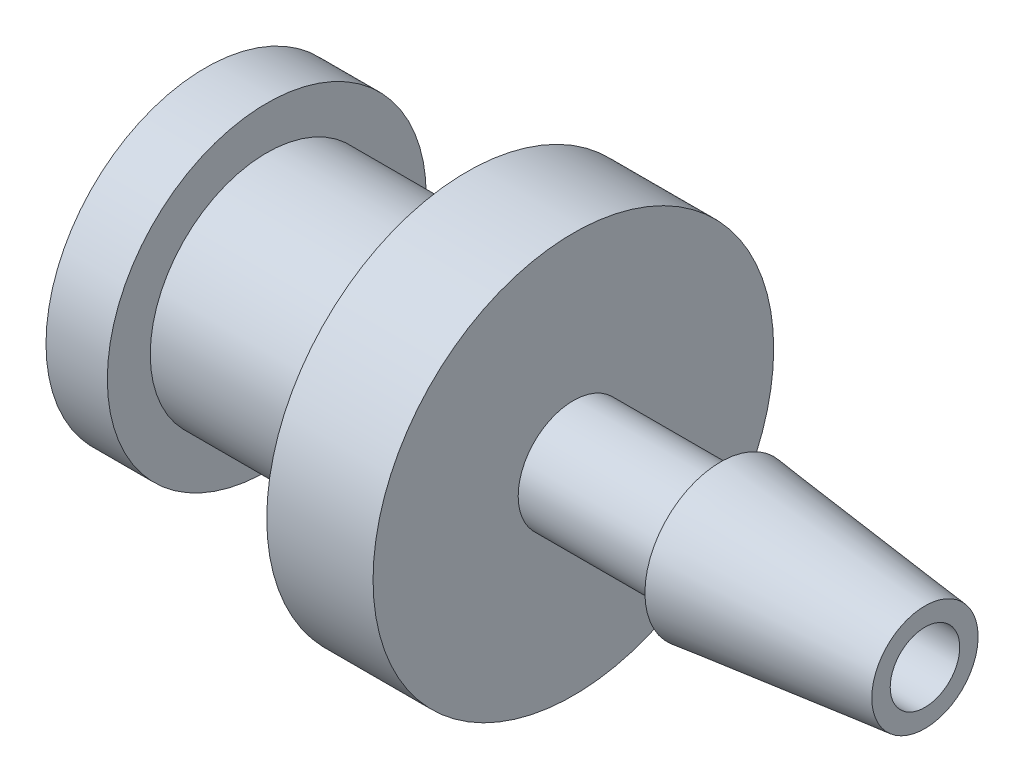
SolidWorks part; units mm, degrees
ref_plane "Płaszczyzna przednia" through (0, 0, 0) normal (0, 0, 1) x (1, 0, 0)
ref_plane "Płaszczyzna górna" through (0, 0, 0) normal (0, 1, 0) x (1, 0, 0)
ref_plane "Płaszczyzna prawa" through (0, 0, 0) normal (1, 0, 0) x (0, 0, -1)
sketch "Sketch1" plane through (0, 0, 0) normal (0, 0, 1) x (1, 0, 0)
  line L0 (-7.1653, 0) -> (17.3074, 0)
  line L1 (17.3074, 0.85) -> (17.3074, 1.3)
  line L2 (17.3074, 1.3) -> (12.3074, 1.85)
  line L3 (12.3074, 1.85) -> (12.3074, 1.35)
  line L4 (12.3074, 1.35) -> (8.7074, 1.35)
  line L5 (8.7074, 1.35) -> (8.7074, 4.9)
  line L6 (8.7074, 4.9) -> (6.1074, 4.9)
  line L7 (6.1074, 4.9) -> (6.1074, 2.85)
  line L8 (6.1074, 2.85) -> (1.2074, 2.85)
  line L9 (1.2074, 2.85) -> (1.2074, 3.9)
  line L10 (1.2074, 3.9) -> (-0.2926, 3.9)
  line L11 (-0.2926, 3.9) -> (-0.2926, 2.05)
  line L12 (-0.2926, 2.05) -> (7.9074, 2.05)
  line L13 (7.9074, 2.05) -> (7.9074, 0.85)
  line L14 (7.9074, 0.85) -> (17.3074, 0.85)
  point P6 (0.4574, 3.9)
  dimension "D1" = 0.85
  dimension "D2" = 1.3
  dimension "D3" = 1.85
  dimension "D4" = 4.9
  dimension "D5" = 2.05
  dimension "D6" = 3.9
  dimension "D7" = 2.85
  dimension "D8" = 0.5
  dimension "D9" = 1.5
  dimension "D10" = 6.4
  dimension "D11" = 17.6
  dimension "D12" = 5
  dimension "D13" = 8.6
  dimension "D14" = 8.2
revolve "Revolve1" add sketch "Sketch1" angle 360 about L0
